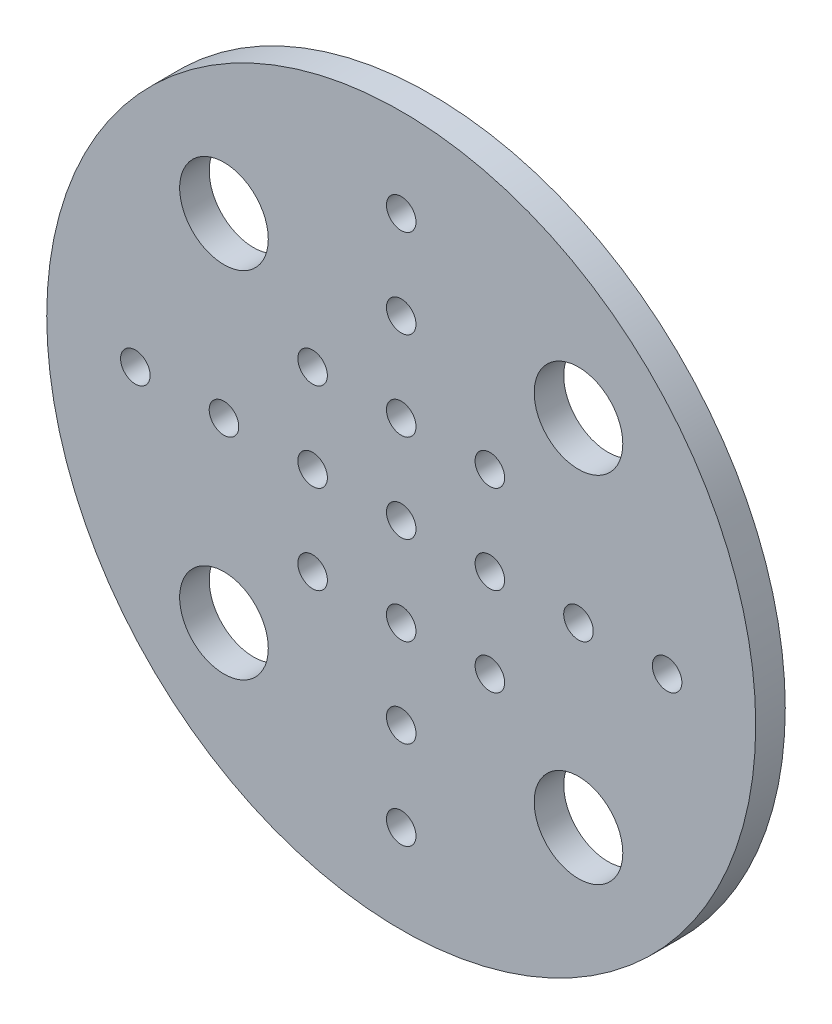
SolidWorks part; units mm, degrees
ref_plane "Alzado" through (0, 0, 0) normal (0, 0, 1) x (1, 0, 0)
ref_plane "Planta" through (0, 0, 0) normal (0, 1, 0) x (1, 0, 0)
ref_plane "Vista lateral" through (0, 0, 0) normal (1, 0, 0) x (0, 0, -1)
sketch "Model" plane through (0, 0, 0) normal (0, 0, 1) x (1, 0, 0)
  circle A0 centre (207.2595, 302.7868) radius 4.5
  circle A1 centre (207.2595, 266.7868) radius 4.5
  circle A2 centre (243.2595, 266.7868) radius 4.5
  circle A3 centre (243.2595, 302.7868) radius 4.5
  circle A4 centre (225.2595, 284.7868) radius 1.5
  circle A5 centre (225.2595, 275.7868) radius 1.5
  circle A6 centre (225.2595, 293.7868) radius 1.5
  circle A7 centre (234.2595, 284.7868) radius 1.5
  circle A8 centre (216.2595, 284.7868) radius 1.5
  circle A9 centre (225.2595, 284.7868) radius 36
  circle A10 centre (243.2595, 284.7868) radius 1.5
  circle A11 centre (252.2595, 284.7868) radius 1.5
  circle A12 centre (198.2595, 284.7868) radius 1.5
  circle A13 centre (207.2595, 284.7868) radius 1.5
  circle A14 centre (225.2595, 302.7868) radius 1.5
  circle A15 centre (225.2595, 311.7868) radius 1.5
  circle A16 centre (225.2595, 266.7868) radius 1.5
  circle A17 centre (225.2595, 257.7868) radius 1.5
  circle A18 centre (216.2595, 275.7868) radius 1.5
  circle A19 centre (234.2595, 293.7868) radius 1.5
  circle A20 centre (234.2595, 275.7868) radius 1.5
  circle A21 centre (216.2595, 293.7868) radius 1.5
extrude "Saliente-Extruir1" add sketch "Model" along normal blind 3
